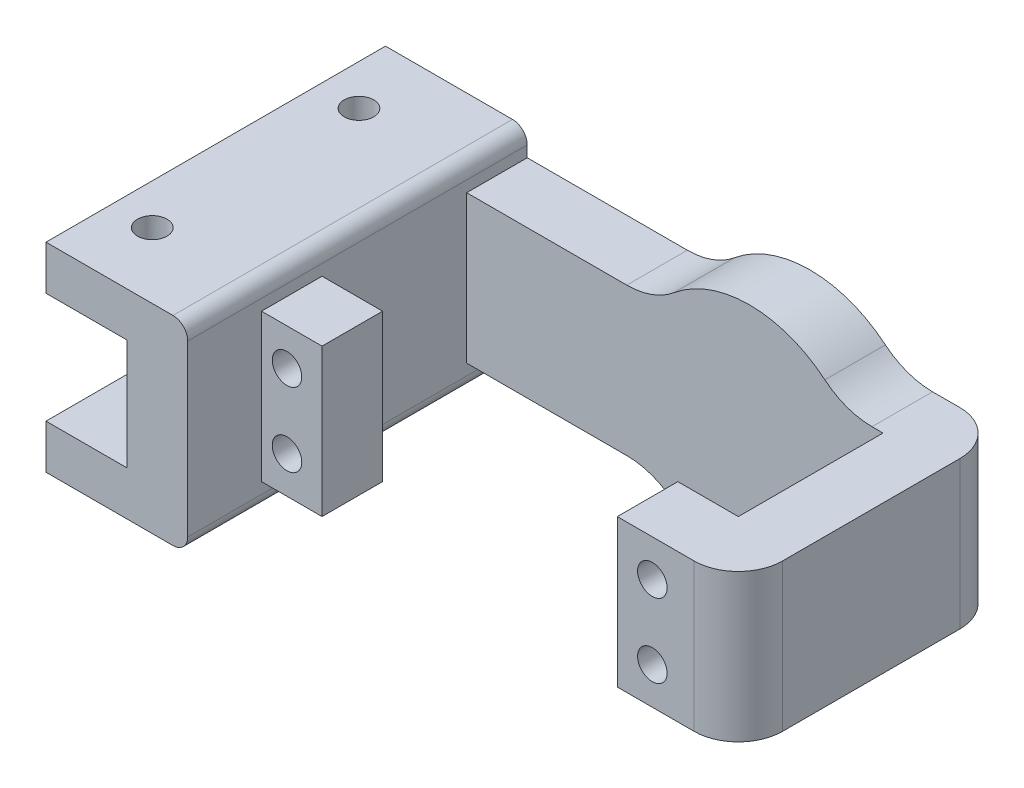
SolidWorks part; units mm, degrees
ref_plane "Piano frontale" through (0, 0, 0) normal (0, 0, 1) x (1, 0, 0)
ref_plane "Piano superiore" through (0, 0, 0) normal (0, 1, 0) x (1, 0, 0)
ref_plane "Piano destro" through (0, 0, 0) normal (1, 0, 0) x (0, 0, -1)
sketch "Schizzo1" plane through (0, 0, 0) normal (0, 0, 1) x (1, 0, 0)
  line L0 (0, 0) -> (64.6, 0)
  line L1 (64.6, 0) -> (64.6, 20)
  line L2 (64.6, 20) -> (0, 20)
  line L3 (0, 20) -> (0, 0)
  dimension "D1" = 64.6
  dimension "D2" = 20
extrude "Estrusione-Estrusione1" add sketch "Schizzo1" along normal blind 8.2
sketch "Schizzo2" plane through (0, 0, 8.2) normal (0, 0, 1) x (1, 0, 0)
  line L0 (0, 20) -> (0, 0)
  line L1 (0, 0) -> (8.2, 0)
  line L2 (0, 0) -> (64.6, 0) construction
  line L3 (8.2, 0) -> (8.2, 20)
  line L4 (64.6, 20) -> (0, 20) construction
  line L5 (8.2, 20) -> (0, 20)
  dimension "D1" = 8.2
extrude "Estrusione-Estrusione2" add sketch "Schizzo2" along normal blind 27.8
sketch "Schizzo3" plane through (0, 0, 8.2) normal (0, 0, 1) x (1, 0, 0)
  line L0 (64.6, 20) -> (64.6, 0)
  line L1 (64.6, 0) -> (56.4, 0)
  line L2 (8.2, 0) -> (64.6, 0) construction
  line L3 (56.4, 0) -> (56.4, 20)
  line L4 (64.6, 20) -> (8.2, 20) construction
  line L5 (56.4, 20) -> (64.6, 20)
  dimension "D1" = 8.2
extrude "Estrusione-Estrusione3" add sketch "Schizzo3" along normal blind 27.8
sketch "Schizzo4" plane through (56.4, 0, 0) normal (-1, 0, 0) x (0, 0, 1)
  line L0 (36, 20) -> (27.8, 20)
  line L1 (36, 20) -> (8.2, 20) construction
  line L2 (27.8, 20) -> (27.8, 0)
  line L3 (36, 0) -> (8.2, 0) construction
  line L4 (27.8, 0) -> (36, 0)
  line L5 (36, 0) -> (36, 20)
  dimension "D1" = 8.2
extrude "Estrusione-Estrusione4" add sketch "Schizzo4" along normal blind 8.2
sketch "Schizzo5" plane through (0, 0, 0) normal (-1, 0, 0) x (0, 0, 1)
  line L0 (36, 0) -> (0, 0)
  line L1 (0, 0) -> (0, 20)
  line L2 (0, 20) -> (36, 20)
  line L3 (36, 20) -> (36, 0)
extrude "Estrusione-Estrusione5" add sketch "Schizzo5" along normal blind 8.2
sketch "Schizzo6" plane through (0, 0, 0) normal (0, -1, 0) x (1, 0, 0)
  line L0 (48.2, 27.8) -> (0, 27.8)
  line L1 (0, 27.8) -> (0, 8.2)
  line L2 (0, 8.2) -> (48.2, 8.2)
  line L3 (8.2, 8.2) -> (56.4, 8.2) construction
  line L4 (48.2, 8.2) -> (48.2, 27.8)
  line L5 (8.2, 36) -> (8.2, 8.2) construction
  dimension "D1" = 8.2
extrude "Taglio-Estrusione1" cut sketch "Schizzo6" against normal through all
hole_wizard "Ø4.0 (4) Diameter Hole2" positions "Schizzo7" profile "Schizzo8" hole size "Ø4.0" standard "ISO"
sketch "Schizzo7" plane through (0, 0, 36) normal (0, 0, 1) x (1, 0, 0)
  line L0 (8.2, 20) -> (-8.2, 20) construction
  line L3 (64.6, 20) -> (48.2, 20) construction
  line L4 (48.2, 0) -> (48.2, 20) construction
  point P0 (52.95, 5)
  point P2 (3.45, 5)
  point P4 (3.45, 15)
  point P6 (52.95, 15)
  dimension "D1" = 10
  dimension "D2" = 10
  dimension "D3" = 49.5
  dimension "D4" = 49.5
  dimension "D5" = 5
  dimension "D6" = 0
  dimension "D7" = 4.75
  dimension "D8" = 5
sketch "Schizzo8" plane through (52.95, 5, 36) normal (1, 0, 0) x (0, -1, 0)
  line L0 (0, 0) -> (0, 8.2)
  line L1 (0, 8.2) -> (2, 8.2)
  line L2 (2, 8.2) -> (2, 0)
  line L5 (2, 0) -> (0, 0)
  line L11 (0, -6.35) -> (0, 107.95) construction
  dimension "Thru Hole Dia." = 4
  dimension "Thru Hole Depth" = 8.2
sketch "Schizzo11" plane through (0, 0, 0) normal (0, 0, -1) x (-1, 0, 0)
  line L0 (8.2, 0) -> (-64.6, 0) construction
  line L1 (-64.6, 0) -> (-64.6, 20) construction
  circle A0 centre (-38.3, 10) radius 16
  dimension "D1" = 10
  dimension "D2" = 26.3
extrude "Estrusione-Estrusione6" add sketch "Schizzo11" against normal blind 8.2
fillet "Raccordo1" radius 10 3 edges at (50.79, 0, 4.1) (25.81, 0, 4.1) (50.79, 20, 4.1)
hole_wizard "Ø22.0 (22) Diameter Hole1" positions "Schizzo12" profile "Schizzo13" hole size "Ø22.0" standard "ISO"
sketch "Schizzo12" plane through (0, 0, 0) normal (0, 0, -1) x (-1, 0, 0)
  point P0 (-38.3, 10)
sketch "Schizzo13" plane through (38.3, 10, 0) normal (1, 0, 0) x (0, 1, 0)
  line L0 (0, 0) -> (0, 16.6095)
  line L1 (0, 16.6095) -> (11, 10)
  line L2 (11, 10) -> (11, 0)
  line L5 (11, 0) -> (0, 0)
  line L10 (0, 16.6095) -> (-11, 10) construction
  line L11 (0, -6.35) -> (0, 107.95) construction
  dimension "Hole Dia." = 22
  dimension "Hole Depth" = 10
  dimension "Drill Angle" = 118
fillet "Raccordo3" radius 6 2 edges at (64.6, 10, 0) (64.6, 10, 36)
sketch "Schizzo15" plane through (0, 0, 0) normal (0, -1, 0) x (1, 0, 0)
  line L0 (0, 0) -> (0, 36)
  line L2 (-8.2, 36) -> (8.2, 36) construction
  line L3 (0, 36) -> (-8.2, 36)
  line L4 (-8.2, 36) -> (-8.2, 0)
  line L5 (-8.2, 0) -> (0, 0)
extrude "Estrusione-Estrusione7" add sketch "Schizzo15" along normal blind 3.5
sketch "Schizzo16" plane through (0, 20, 0) normal (0, 1, 0) x (1, 0, 0)
  line L0 (-8.2, 0) -> (-8.2, -36)
  line L1 (-8.2, -36) -> (0, -36)
  line L2 (8.2, -36) -> (-8.2, -36) construction
  line L3 (0, -36) -> (0, 0)
  line L4 (0, 0) -> (-8.2, 0)
extrude "Estrusione-Estrusione8" add sketch "Schizzo16" along normal blind 3.5
sketch "Schizzo17" plane through (-8.2, 0, 0) normal (-1, 0, 0) x (0, 0, 1)
  line L0 (0, 17.5) -> (36, 17.5)
  line L1 (0, 23.5) -> (0, -3.5) construction
  line L2 (36, -3.5) -> (36, 23.5) construction
  line L3 (36, 17.5) -> (36, 23.5)
  line L4 (36, 23.5) -> (0, 23.5)
  line L5 (0, 23.5) -> (0, 17.5)
  line L6 (0, 2.5) -> (36, 2.5)
  line L7 (36, 2.5) -> (36, -3.5)
  line L8 (36, -3.5) -> (0, -3.5)
  line L9 (0, -3.5) -> (0, 2.5)
  dimension "D1" = 6
  dimension "D2" = 6
extrude "Estrusione-Estrusione9" add sketch "Schizzo17" along normal blind 11 contours L6 L7 L8 L9 | L5 L0 L3 L4
fillet "Raccordo6" radius 2 2 edges at (0, -3.5, 18) (0, 23.5, 18)
sketch "Schizzo23" plane through (0, 0, 8.2) normal (0, 0, 1) x (1, 0, 0)
  circle A0 centre (38.3, 10) radius 11
extrude "Estrusione-Estrusione10" add sketch "Schizzo23" against normal blind 2.2
sketch "Schizzo24" plane through (0, 0, 36) normal (0, 0, 1) x (1, 0, 0)
  line L0 (-2, 23.5) -> (-19.2, 23.5)
  line L1 (-19.2, 23.5) -> (-19.2, 17.5)
  line L2 (-19.2, 17.5) -> (-8.2, 17.5)
  line L3 (-8.2, 17.5) -> (-8.2, 2.5)
  line L4 (-8.2, 2.5) -> (-19.2, 2.5)
  line L5 (-19.2, 2.5) -> (-19.2, -3.5)
  line L6 (-19.2, -3.5) -> (-2, -3.5)
  line L7 (0, 21.5) -> (0, -1.5)
  arc A0 (-2, -3.5) -> (0, -1.5) centre (-2, -1.5) ccw
  arc A1 (-2, 23.5) -> (0, 21.5) centre (-2, 21.5) cw
extrude "Estrusione-Estrusione11" add sketch "Schizzo24" along normal blind 10
hole_wizard "Ø4.0 (4) Diameter Hole1" positions "Schizzo25" profile "Schizzo26" hole size "Ø4.0" standard "ISO" end condition through all
sketch "Schizzo25" plane through (0, -3.5, 0) normal (0, -1, 0) x (-1, 0, 0)
  line L0 (19.2, -46) -> (19.2, 0) construction
  line L1 (19.2, 0) -> (2, 0) construction
  point P0 (13.7, -37.1)
  point P2 (13.7, -9.1)
  dimension "D1" = 5.5
  dimension "D2" = 5.5
  dimension "D3" = 28
  dimension "D4" = 9.1
sketch "Schizzo26" plane through (-13.7, -3.5, 37.1) normal (1, 0, 0) x (0, 0, -1)
  line L0 (0, 0) -> (0, 29.5)
  line L1 (0, 29.5) -> (2, 29.5)
  line L2 (2, 29.5) -> (2, 0)
  line L5 (2, 0) -> (0, 0)
  line L11 (0, -6.35) -> (0, 107.95) construction
  dimension "Thru Hole Dia." = 4
  dimension "Thru Hole Depth" = 29.5
